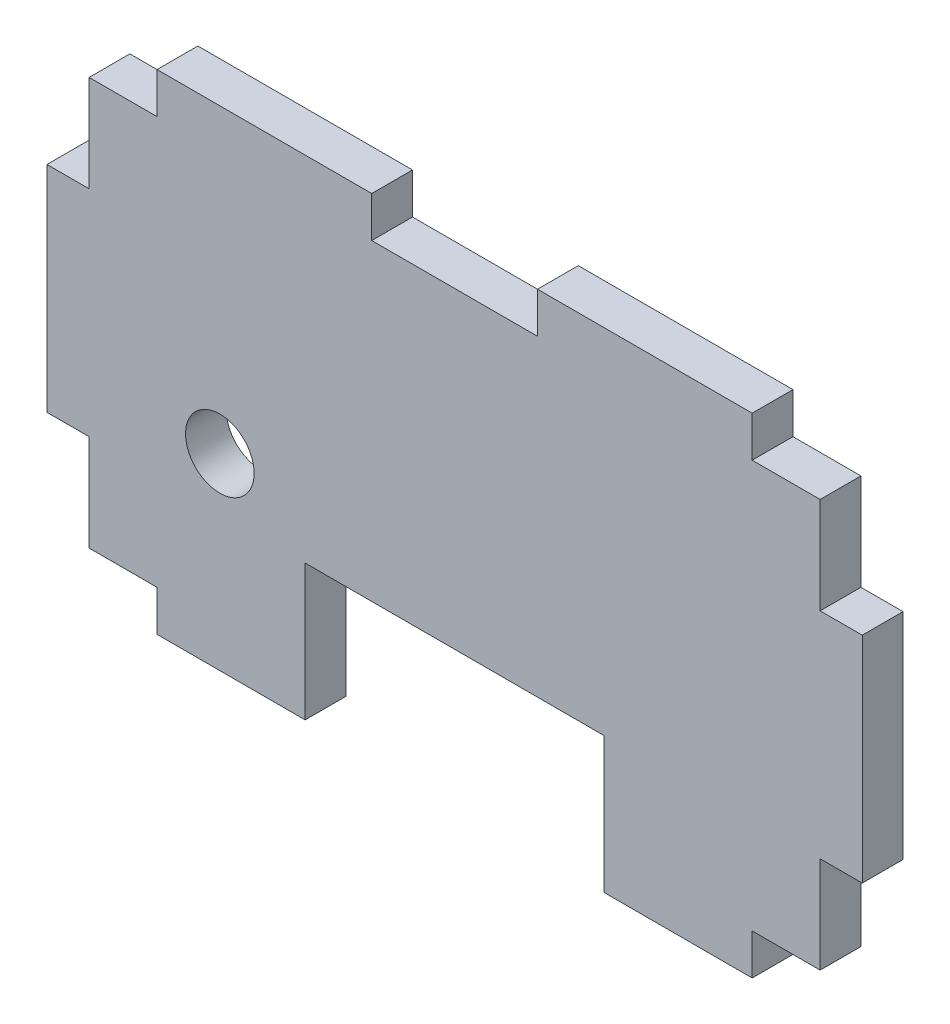
SolidWorks part; units mm, degrees
ref_plane "Front Plane" through (0, 0, 0) normal (0, 0, 1) x (1, 0, 0)
ref_plane "Top Plane" through (0, 0, 0) normal (0, 1, 0) x (1, 0, 0)
ref_plane "Right Plane" through (0, 0, 0) normal (1, 0, 0) x (0, 0, -1)
sketch "Sketch1" plane through (0, 0, 0) normal (0, 0, 1) x (1, 0, 0)
  line L0 (0, 30) -> (5, 30)
  line L1 (5, -3) -> (20.8, -3)
  line L2 (-3.1, 7.1) -> (-3.1, 22.9)
  line L3 (5, 33) -> (20.8, 33)
  line L4 (56.9, 7.1) -> (56.9, 22.9)
  line L5 (5, 30) -> (5, 33)
  line L6 (5, 33) -> (20.8, 33)
  line L7 (20.8, 33) -> (20.8, 30)
  line L8 (20.8, 30) -> (33, 30)
  line L9 (33, 30) -> (33, 33)
  line L10 (33, 33) -> (48.8, 33)
  line L11 (48.8, 33) -> (48.8, 30)
  line L12 (48.8, 30) -> (53.8, 30)
  line L13 (53.8, 30) -> (53.8, 22.9)
  line L14 (53.8, 22.9) -> (56.9, 22.9)
  line L15 (56.9, 22.9) -> (56.9, 7.1)
  line L16 (56.9, 7.1) -> (53.8, 7.1)
  line L17 (53.8, 7.1) -> (53.8, 0)
  line L18 (53.8, 0) -> (48.8, 0)
  line L19 (48.8, 0) -> (48.8, -3)
  line L20 (48.8, -3) -> (33, -3)
  line L21 (33, -3) -> (33, 0)
  line L22 (33, 0) -> (20.8, 0)
  line L23 (20.8, 0) -> (20.8, -3)
  line L24 (20.8, -3) -> (5, -3)
  line L25 (5, -3) -> (5, 0)
  line L26 (5, 0) -> (0, 0)
  line L27 (0, 0) -> (0, 7.1)
  line L28 (0, 7.1) -> (-3.1, 7.1)
  line L29 (-3.1, 7.1) -> (-3.1, 22.9)
  line L30 (-3.1, 22.9) -> (0, 22.9)
  line L31 (0, 22.9) -> (0, 30)
  line L32 (33, 33) -> (48.8, 33)
  line L33 (33, -3) -> (48.8, -3)
  line L39 (15.9, 7) -> (37.9, 7)
  line L40 (15.9, 7) -> (15.9, -3)
  line L41 (15.9, -3) -> (37.9, -3)
  line L42 (37.9, 7) -> (37.9, -3)
  circle A0 centre (9.621, 10.8332) radius 2.525
  point P4 (26.9, 7)
  point P7 (26.9, 30)
  point P15 (9.621, 10.8332)
  dimension "D9" = 5.05
  dimension "D1" = 60
  dimension "D2" = 36
  dimension "D3" = 15.8
  dimension "D4" = 12.2
  dimension "D5" = 3
  dimension "D6" = 3.1
  dimension "D7" = 10
  dimension "D8" = 22
extrude "Boss-Extrude1" add sketch "Sketch1" along normal blind 3 contours L31 L30 L2 L28 L27 L26 L25 L1 L23 L22 L21 L20 L19 L18 L17 L16 L4 L14 L13 L12 L11 L10 L9 L8 L7 L3 L5 L0
